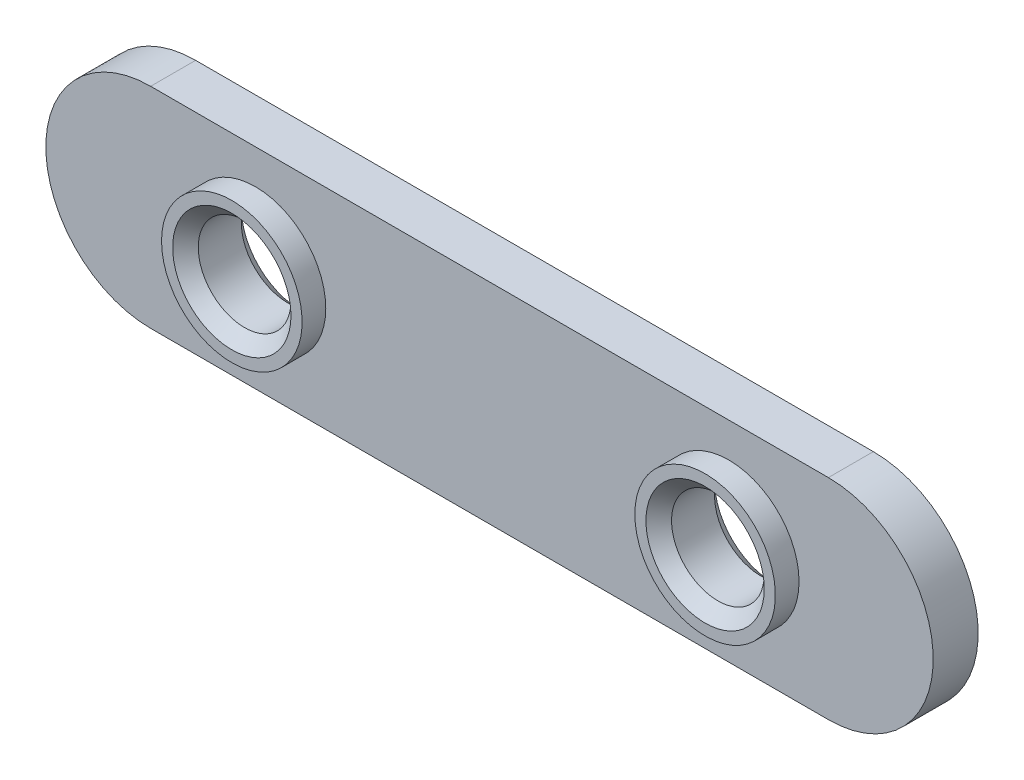
SolidWorks part; units mm, degrees
ref_plane "Front Plane" through (0, 0, 0) normal (0, 0, 1) x (1, 0, 0)
ref_plane "Top Plane" through (0, 0, 0) normal (0, 1, 0) x (1, 0, 0)
ref_plane "Right Plane" through (0, 0, 0) normal (1, 0, 0) x (0, 0, -1)
ref_plane "Plane1" through (0, 0, 1.2065) normal (0, 0, 1) x (1, 0, 0)
sketch "Sketch1" plane through (0, 0, 1.2065) normal (0, 0, 1) x (1, 0, 0)
  line L0 (30.7467, 5.6261) -> (-5.6261, 5.6261)
  line L1 (-5.6261, -5.6261) -> (30.7467, -5.6261)
  arc A0 (-5.6261, 5.6261) -> (-5.6261, -5.6261) centre (-5.6261, 0) ccw
  arc A1 (30.7467, -5.6261) -> (30.7467, 5.6261) centre (30.7467, 0) ccw
extrude "Boss-Extrude1" add sketch "Sketch1" against normal blind 2.413
ref_plane "Plane2" through (0, 0, 0) normal (0, -1, 0) x (1, 0, 0)
sketch "Sketch2" plane through (0, 0, 0) normal (0, -1, 0) x (1, 0, 0)
  line L0 (3.7719, 2.4765) -> (0, 2.4765)
  line L1 (0, 2.4765) -> (0, 1.2065)
  line L2 (0, 1.2065) -> (3.7719, 1.2065)
  line L3 (3.7719, 1.2065) -> (3.7719, 2.4765)
  line L4 (0, 2.4765) -> (0, 1.2065) construction
revolve "Revolve1" add sketch "Sketch2" angle 360 about L4
sketch "Sketch3" plane through (0, 0, 0) normal (0, -1, 0) x (1, 0, 0)
  line L0 (29.1719, 2.4765) -> (25.4, 2.4765)
  line L1 (25.4, 2.4765) -> (25.4, 1.2065)
  line L2 (25.4, 1.2065) -> (29.1719, 1.2065)
  line L3 (29.1719, 1.2065) -> (29.1719, 2.4765)
  line L4 (25.4, 2.4765) -> (25.4, 1.2065) construction
revolve "Revolve2" add sketch "Sketch3" angle 360 about L4
hole_wizard "Hole1" positions "Sketch5" profile "Sketch4" legacy
sketch "Sketch5" plane through (0, 0, 2.4765) normal (0, 0, 1) x (1, 0, 0)
  point P0 (0, 0)
  point P1 (25.4, 0)
sketch "Sketch4" plane through (0, 0, 2.4765) normal (1, 0, 0) x (0, -1, 0)
  line L0 (0, 0) -> (0, 3.683)
  line L1 (0, 3.683) -> (2.4879, 3.683)
  line L2 (2.4879, 3.683) -> (2.4879, 0.6871)
  line L3 (2.4879, 0.6871) -> (3.175, 0)
  line L4 (3.175, 0) -> (0, 0)
  line L5 (0, -6.4453) -> (0, 115.525) construction
  line L6 (-2.4879, 0.6871) -> (-3.175, 0) construction
  dimension "Diameter" = 4.9759
  dimension "Depth" = 3.683
  dimension "C-Sink Angle" = 90
  dimension "C-Sink Diameter" = 6.35
chamfer "Chamfer1" distance 0.6871 angle 45 2 edges at (27.8879, 0, -1.2065) (2.4879, 0, -1.2065)
